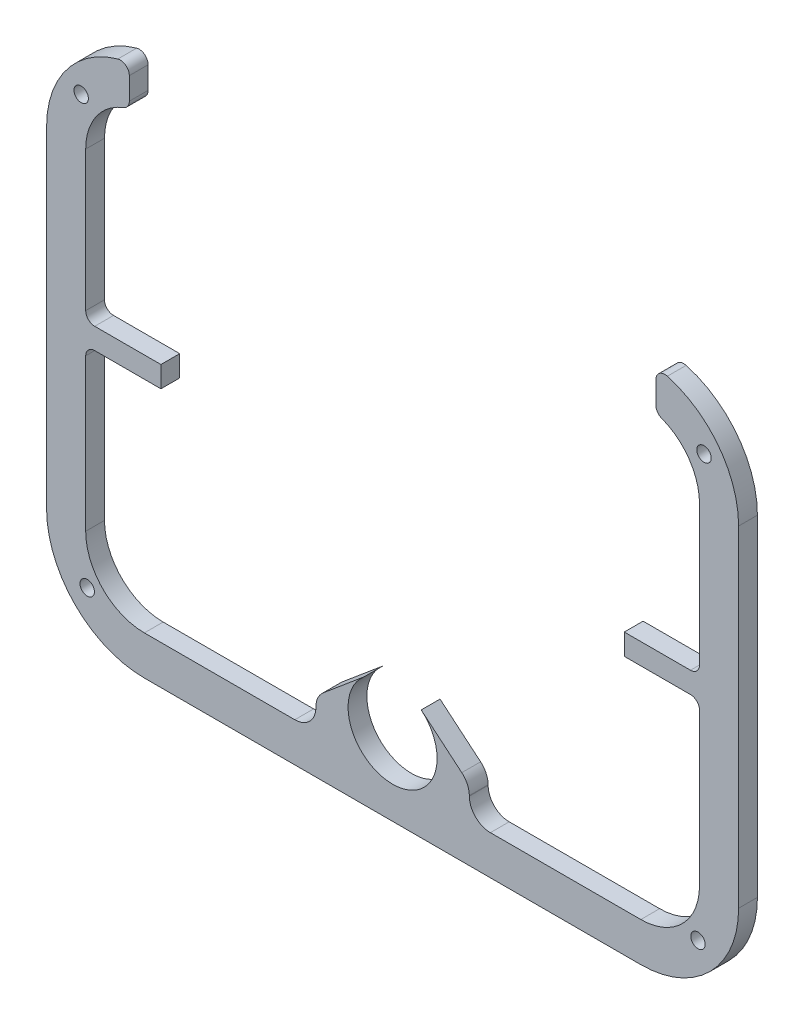
SolidWorks part; units mm, degrees
material "Delrin 2700 NC010, Low Viscosity Acetal Copolymer (SS)"
ref_plane "Front Plane" through (0, 0, 0) normal (0, 0, 1) x (1, 0, 0)
ref_plane "Top Plane" through (0, 0, 0) normal (0, 1, 0) x (1, 0, 0)
ref_plane "Right Plane" through (0, 0, 0) normal (1, 0, 0) x (0, 0, -1)
sketch "Sketch1" plane through (0, 0, 0) normal (0, 0, 1) x (1, 0, 0)
  line L0 (-20.955, -18.923) -> (-9.6321, -18.923)
  line L1 (20.955, 22.225) -> (-20.955, 22.225)
  line L2 (29.21, 13.97) -> (29.21, -13.97)
  line L3 (20.955, -22.225) -> (-20.955, -22.225)
  line L4 (-29.21, 13.97) -> (-29.21, -13.97)
  line L5 (29.21, 22.225) -> (-29.21, -22.225) construction
  line L6 (29.21, -22.225) -> (-29.21, 22.225) construction
  line L7 (9.6321, -18.923) -> (20.955, -18.923)
  line L8 (-25.908, -0.381) -> (-19.558, -0.381)
  line L9 (25.908, 1.397) -> (19.558, 1.397)
  line L10 (-25.908, 13.97) -> (-25.908, -13.97)
  line L11 (-1000, 0) -> (49000, 0) construction
  line L12 (-25.908, 0) -> (-25.908, -1.27)
  line L13 (25.908, 13.97) -> (25.908, -13.97)
  line L14 (20.955, 18.923) -> (-20.955, 18.923)
  line L15 (25.908, 1.397) -> (25.908, -0.381)
  line L16 (25.908, -0.381) -> (19.558, -0.381)
  line L17 (19.558, 1.397) -> (19.558, -0.381)
  line L18 (0, 18.923) -> (0, -18.415) construction
  line L19 (-19.558, 1.397) -> (-19.558, -0.381)
  line L20 (-25.908, 1.397) -> (-19.558, 1.397)
  line L21 (2.4164, -12.8683) -> (9.6321, -18.923)
  line L22 (-2.4164, -12.8683) -> (-9.6321, -18.923)
  line L36 (20.955, -18.923) -> (-20.955, -18.923) construction
  arc A0 (-2.4164, -12.8683) -> (2.4164, -12.8683) centre (0, -15.748) ccw
  arc A1 (-20.955, 22.225) -> (-29.21, 13.97) centre (-20.955, 13.97) ccw
  arc A2 (20.955, 22.225) -> (29.21, 13.97) centre (20.955, 13.97) cw
  arc A3 (29.21, -13.97) -> (20.955, -22.225) centre (20.955, -13.97) cw
  arc A4 (-20.955, -22.225) -> (-29.21, -13.97) centre (-20.955, -13.97) cw
  arc A7 (20.955, 18.923) -> (25.908, 13.97) centre (20.955, 13.97) cw
  arc A8 (-20.955, 18.923) -> (-25.908, 13.97) centre (-20.955, 13.97) ccw
  arc A13 (-20.955, -18.923) -> (-25.908, -13.97) centre (-20.955, -13.97) cw construction
  arc A14 (25.908, -13.97) -> (20.955, -18.923) centre (20.955, -13.97) cw construction
  arc A15 (-25.908, -13.97) -> (-20.955, -18.923) centre (-20.955, -13.97) ccw
  arc A16 (20.955, -18.923) -> (25.908, -13.97) centre (20.955, -13.97) ccw
  point P0 (0, 0)
  dimension "D4" = 7.5184
  dimension "D6" = 8.255
  dimension "D7" = 8.255
  dimension "D8" = 8.255
  dimension "D9" = 8.255
  dimension "D1" = 58.42
  dimension "D2" = 44.45
  dimension "D10" = 3.302
  dimension "D3" = 3.175
  dimension "D13" = 15.748
  dimension "D14" = 1.778
  dimension "D15" = 21.844
  dimension "D16" = 6.35
extrude "Boss-Extrude1" add sketch "Sketch1" along normal blind 1.5875
sketch "Sketch2" plane through (0, 0, 1.5875) normal (0, 0, 1) x (1, 0, 0)
  line L1 (-9.6321, -18.923) -> (-6.477, -18.923)
  line L2 (-9.6321, -18.923) -> (-9.6321, -16.2756)
  line L3 (-9.6321, -16.2756) -> (-6.477, -16.2756)
  line L4 (-6.477, -18.923) -> (-6.477, -16.2756)
  line L5 (0, -1000) -> (0, 49000) construction
  line L6 (9.6321, -18.923) -> (9.6321, -16.2756)
  line L7 (9.6321, -16.2756) -> (6.477, -16.2756)
  line L8 (6.477, -18.923) -> (6.477, -16.2756)
  line L9 (9.6321, -18.923) -> (6.477, -18.923)
  line L10 (-29.21, 13.97) -> (-29.21, -13.97) construction
  line L11 (-20.955, 18.923) -> (20.955, 18.923)
  line L12 (-22.225, 18.7574) -> (-22.225, 22.225)
  line L13 (-22.225, 22.225) -> (22.225, 22.225)
  line L14 (22.225, 18.7574) -> (22.225, 22.225)
  line L16 (20.955, 18.923) -> (-20.955, 18.923) construction
  line L17 (-2.4164, -12.8683) -> (-9.6321, -18.923) construction
  line L18 (20.955, 22.225) -> (-20.955, 22.225) construction
  arc A0 (25.908, 13.97) -> (20.955, 18.923) centre (20.955, 13.97) ccw construction
  arc A1 (-20.955, 18.923) -> (-25.908, 13.97) centre (-20.955, 13.97) ccw construction
  arc A2 (22.225, 18.7574) -> (20.955, 18.923) centre (20.955, 13.97) ccw
  arc A3 (-20.955, 18.923) -> (-22.225, 18.7574) centre (-20.955, 13.97) ccw
  point P25 (0, 22.225)
  point P29 (0, 0)
  dimension "D1" = 6.477
  dimension "D2" = 6.985
extrude "Cut-Extrude1" cut sketch "Sketch2" against normal up to next
fillet "Fillet1" radius 1.778 4 edges at (6.477, -18.923, 0.7937) (6.477, -16.2756, 0.7937) (-6.477, -18.923, 0.7937) (-6.477, -16.2756, 0.7937)
fillet "Fillet2" radius 0.762 4 edges at (22.225, 22.1267, 0.7937) (22.225, 18.7574, 0.7937) (-22.225, 18.7574, 0.7937) (-22.225, 22.1267, 0.7937)
fillet "Fillet3" radius 0.762 4 edges at (25.908, -0.381, 0.7937) (25.908, 1.397, 0.7937) (-25.908, 1.397, 0.7937) (-25.908, -0.381, 0.7937)
sketch "Sketch3" plane through (0, 0, 1.5875) normal (0, 0, 1) x (1, 0, 0)
  circle A0 centre (-25.019, -16.51) radius 0.6096 construction
  circle A1 centre (-25.019, 16.256) radius 0.6096 construction
  circle A2 centre (25.019, 16.256) radius 0.6096 construction
  circle A3 centre (25.019, -16.51) radius 0.6096 construction
  circle A4 centre (-25.019, -16.51) radius 0.6096 construction
  circle A5 centre (-25.019, 16.256) radius 0.6096 construction
  circle A6 centre (25.019, 16.256) radius 0.6096 construction
  circle A7 centre (25.019, -16.51) radius 0.6096 construction
  circle A8 centre (-26.289, 17.78) radius 0.6096
  circle A9 centre (-25.781, -18.034) radius 0.6096
  circle A10 centre (26.289, 17.78) radius 0.6096
  circle A11 centre (25.781, -18.034) radius 0.6096
  dimension "D1" = 1.524
  dimension "D2" = 1.27
  dimension "D3" = 1.524
  dimension "D4" = 0.762
  dimension "D5" = 1.27
  dimension "D6" = 0.762
extrude "Cut-Extrude2" cut sketch "Sketch3" against normal up to surface (1.5875 mm away) up to face at (0, -2.0741, 0)
